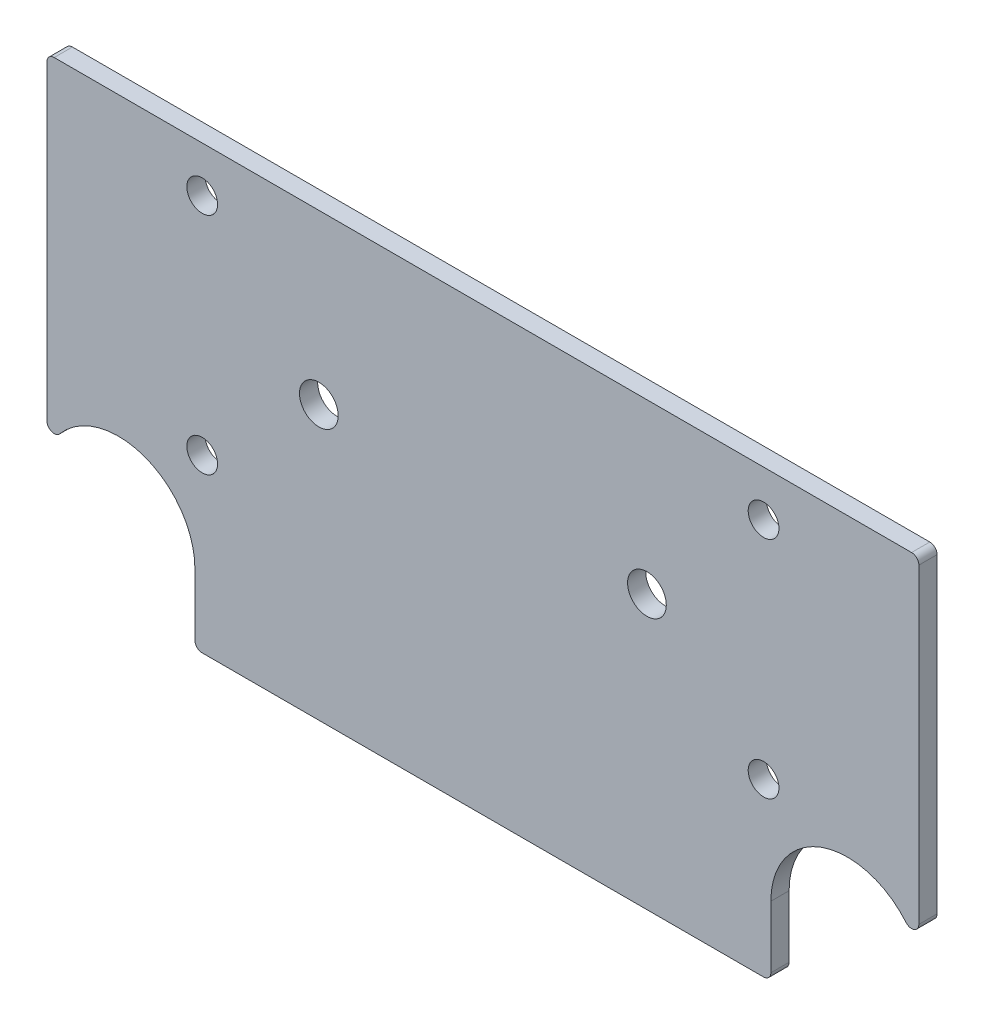
SolidWorks part; units mm, degrees
material "PC High Viscosity"
ref_plane "Front Plane" through (0, 0, 0) normal (0, 0, 1) x (1, 0, 0)
ref_plane "Top Plane" through (0, 0, 0) normal (0, 1, 0) x (1, 0, 0)
ref_plane "Right Plane" through (0, 0, 0) normal (1, 0, 0) x (0, 0, -1)
sketch "Sketch1" plane through (0, 0, 0) normal (0, 0, 1) x (1, 0, 0)
  line L0 (127, 0) -> (-127, 0) construction
  line L1 (101.6, -357.1875) -> (101.6, 357.1875) construction
  line L2 (152.4, 0) -> (152.4, 357.1875) construction
  line L3 (-101.6, -357.1875) -> (-101.6, 357.1875) construction
  line L4 (-152.4, -357.1875) -> (-152.4, 357.1875) construction
  line L5 (101.6, 59.0332) -> (-101.6, 262.2332) construction
  line L6 (101.6, 94.9543) -> (-101.6, 298.1543) construction
  line L7 (0, 196.5543) -> (0, 160.6332) construction
  line L8 (0, 178.5938) -> (152.4, 178.5938) construction
  line L9 (105.003, 12.7) -> (-105.003, 12.7) construction
  line L10 (105.003, -12.7) -> (-105.003, -12.7) construction
  line L11 (-101.6, 59.0332) -> (101.6, 262.2332) construction
  line L12 (-101.6, 94.9543) -> (101.6, 298.1543) construction
  line L13 (152.4, 0) -> (152.4, -357.1875) construction
  line L14 (-101.6, -94.9543) -> (101.6, -298.1543) construction
  line L15 (-101.6, -59.0332) -> (101.6, -262.2332) construction
  line L16 (101.6, -94.9543) -> (-101.6, -298.1543) construction
  line L17 (101.6, -59.0332) -> (-101.6, -262.2332) construction
  line L18 (-179.07, -25.4) -> (-179.07, 128.4583)
  line L19 (-179.07, 128.4583) -> (179.07, 128.4583)
  line L20 (179.07, 128.4583) -> (179.07, -25.4)
  line L21 (179.07, -25.4) -> (153.67, -25.4)
  line L22 (153.67, -25.4) -> (153.67, -1.27)
  line L23 (100.33, -1.27) -> (100.33, -25.4)
  line L24 (100.33, -25.4) -> (-100.33, -25.4)
  line L25 (-100.33, -25.4) -> (-100.33, -1.27)
  line L26 (-153.67, -1.27) -> (-153.67, -25.4)
  line L27 (-179.07, -25.4) -> (-153.67, -25.4)
  circle A0 centre (-127, 0) radius 25.4 construction
  circle A1 centre (127, 0) radius 25.4 construction
  circle A2 centre (-127, 357.1875) radius 25.4 construction
  circle A3 centre (127, 357.1875) radius 25.4 construction
  arc A4 (100.33, -1.27) -> (153.67, -1.27) centre (127, -1.27) cw
  arc A5 (-100.33, -1.27) -> (-153.67, -1.27) centre (-127, -1.27) ccw
  circle A6 centre (96.139, 108.1383) radius 5.461 construction
  point P23 (0, 178.5938)
  point P33 (101.6, 0)
  point P37 (-152.4, 0)
  point P38 (-101.6, 0)
  point P53 (127, 25.4)
  point P54 (127, 25.4)
  dimension "D2" = 50.8
  dimension "D7" = 26.67
  dimension "D9" = 25.4
  dimension "D10" = 10.922
  dimension "D1" = 254
  dimension "D3" = 357.1875
  dimension "D4" = 25.4
  dimension "D5" = 45
  dimension "D6" = 25.4
  dimension "D8" = 25.4
  dimension "D11" = 20.32
extrude "Boss-Extrude1" add sketch "Sketch1" along normal blind 6.35
sketch "Sketch7" plane through (0, 0, 0) normal (0, 0, -1) x (-1, 0, 0)
  line L0 (-151.892, 128.4583) -> (-151.892, 8.3048)
  line L1 (-152.4, 0) -> (-152.4, 357.1875) construction
  line L2 (-179.07, 128.4583) -> (179.07, 128.4583) construction
  line L3 (0, -25.4) -> (0, 128.4583) construction
  line L4 (100.33, -25.4) -> (-100.33, -25.4) construction
  line L5 (-151.892, 128.4583) -> (-179.07, 128.4583)
  line L6 (-179.07, 128.4583) -> (-179.07, -25.4)
  line L7 (-179.07, -25.4) -> (-153.67, -25.4)
  line L8 (-153.67, -25.4) -> (-153.67, -1.27)
  line L9 (153.67, -25.4) -> (153.67, -1.27)
  line L10 (179.07, -25.4) -> (153.67, -25.4)
  line L11 (179.07, 128.4583) -> (179.07, -25.4)
  line L12 (151.892, 128.4583) -> (179.07, 128.4583)
  line L13 (151.892, 128.4583) -> (151.892, 8.3048)
  arc A0 (-100.33, -1.27) -> (-153.67, -1.27) centre (-127, -1.27) ccw construction
  arc A1 (-153.67, -1.27) -> (-151.892, 8.3048) centre (-127, -1.27) cw
  arc A2 (153.67, -1.27) -> (151.892, 8.3048) centre (127, -1.27) ccw
  dimension "D1" = 0.508
extrude "Cut-Extrude1" cut sketch "Sketch7" against normal through all
hole_wizard "27/64 (0.42188) Diameter Hole1" positions "Sketch2" profile "Sketch3" hole size "27/64" standard "ANSI Inch" end condition through all
sketch "Sketch2" plane through (0, 0, 6.35) normal (0, 0, 1) x (1, 0, 0)
  line L0 (-127, 0) -> (-127, 128.4583) construction
  line L1 (-179.07, 128.4583) -> (179.07, 128.4583) construction
  line L2 (0, 128.4583) -> (0, -25.4) construction
  line L3 (100.33, -25.4) -> (-100.33, -25.4) construction
  line L4 (-101.6, -357.1875) -> (-101.6, 357.1875) construction
  point P0 (-97.79, 34.29)
  point P2 (-97.79, 112.5833)
  point P19 (97.79, 34.29)
  point P22 (97.79, 112.5833)
  dimension "D1" = 15.875
  dimension "D2" = 3.81
  dimension "D3" = 34.29
sketch "Sketch3" plane through (-97.79, 34.29, 6.35) normal (1, 0, 0) x (0, -1, 0)
  line L0 (0, 0) -> (0, 6.35)
  line L1 (0, 6.35) -> (5.3579, 6.35)
  line L2 (5.3579, 6.35) -> (5.3579, 0)
  line L5 (5.3579, 0) -> (0, 0)
  line L11 (0, -6.35) -> (0, 107.95) construction
  dimension "Thru Hole Dia." = 10.7158
  dimension "Thru Hole Depth" = 6.35
fillet "Fillet1" radius 2.54 6 edges at (100.33, -25.4, 3.175) (-100.33, -25.4, 3.175) (-151.892, 8.3048, 3.175) (-151.892, 128.4583, 3.175) (151.892, 128.4583, 3.175) (151.892, 8.3048, 3.175)
hole_wizard "1/2 Clearance Hole1" positions "Sketch4" profile "Sketch5" hole size "1/2" standard "ANSI Inch" end condition through all
sketch "Sketch4" plane through (0, 0, 6.35) normal (0, 0, 1) x (1, 0, 0)
  line L1 (0, 0) -> (0, 160.6332) construction
  line L2 (127, 0) -> (-127, 0) construction
  line L4 (105.003, 12.7) -> (-105.003, 12.7) construction
  line L5 (101.6, -357.1875) -> (101.6, 357.1875) construction
  circle A0 centre (57.15, 69.85) radius 12.7 construction
  point P0 (57.15, 69.85)
  point P18 (-57.15, 69.85)
  dimension "D1" = 25.4
  dimension "D2" = 57.15
  dimension "D3" = 44.45
sketch "Sketch5" plane through (57.15, 69.85, 6.35) normal (1, 0, 0) x (0, -1, 0)
  line L0 (0, 0) -> (0, 6.35)
  line L1 (0, 6.35) -> (6.7462, 6.35)
  line L2 (6.7462, 6.35) -> (6.7462, 0)
  line L5 (6.7462, 0) -> (0, 0)
  line L11 (0, -6.35) -> (0, 107.95) construction
  dimension "Thru Hole Dia." = 13.4925
  dimension "Thru Hole Depth" = 6.35
sketch "Sketch6" plane through (0, 0, 6.35) normal (0, 0, 1) x (1, 0, 0)
  line L0 (-127, 128.4583) -> (-127, 25.4) construction
  line L1 (149.352, 128.4583) -> (-149.352, 128.4583) construction
  arc A1 (-100.33, -1.27) -> (-153.67, -1.27) centre (-127, -1.27) ccw construction
ref_plane "Plane1" through (-127, 0, 0) normal (1, 0, 0) x (0, 0, -1)
